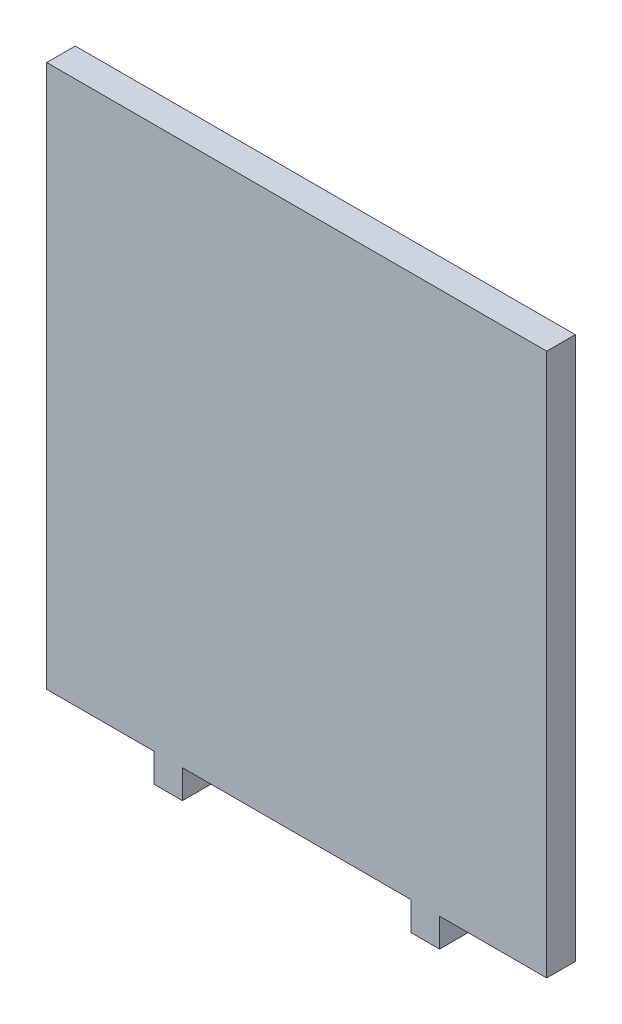
SolidWorks part; units mm, degrees
material "ABS"
ref_plane "Plan de face" through (0, 0, 0) normal (0, 0, 1) x (1, 0, 0)
ref_plane "Plan de dessus" through (0, 0, 0) normal (0, 1, 0) x (1, 0, 0)
ref_plane "Plan de droite" through (0, 0, 0) normal (1, 0, 0) x (0, 0, -1)
sketch "Esquisse1" plane through (0, 0, 0) normal (0, 0, 1) x (1, 0, 0)
  line L0 (16, -38) -> (-16, -38)
  line L1 (35, -38) -> (20, -38)
  line L2 (35, -38) -> (35, 38)
  line L3 (35, 38) -> (-35, 38)
  line L4 (-35, -38) -> (-35, 38)
  line L5 (35, -38) -> (-35, 38) construction
  line L6 (35, 38) -> (-35, -38) construction
  line L8 (-20, -38) -> (-20, -42)
  line L9 (-20, -42) -> (-16, -42)
  line L10 (-16, -38) -> (-16, -42)
  line L12 (20, -38) -> (20, -42)
  line L13 (20, -42) -> (16, -42)
  line L14 (16, -38) -> (16, -42)
  line L15 (-20, -38) -> (-35, -38)
  point P0 (0, 0)
  dimension "D1" = 70
  dimension "D2" = 76
  dimension "D3" = 4
  dimension "D4" = 15
  dimension "D5" = 15
extrude "Boss.-Extru.1" add sketch "Esquisse1" along normal blind 4
